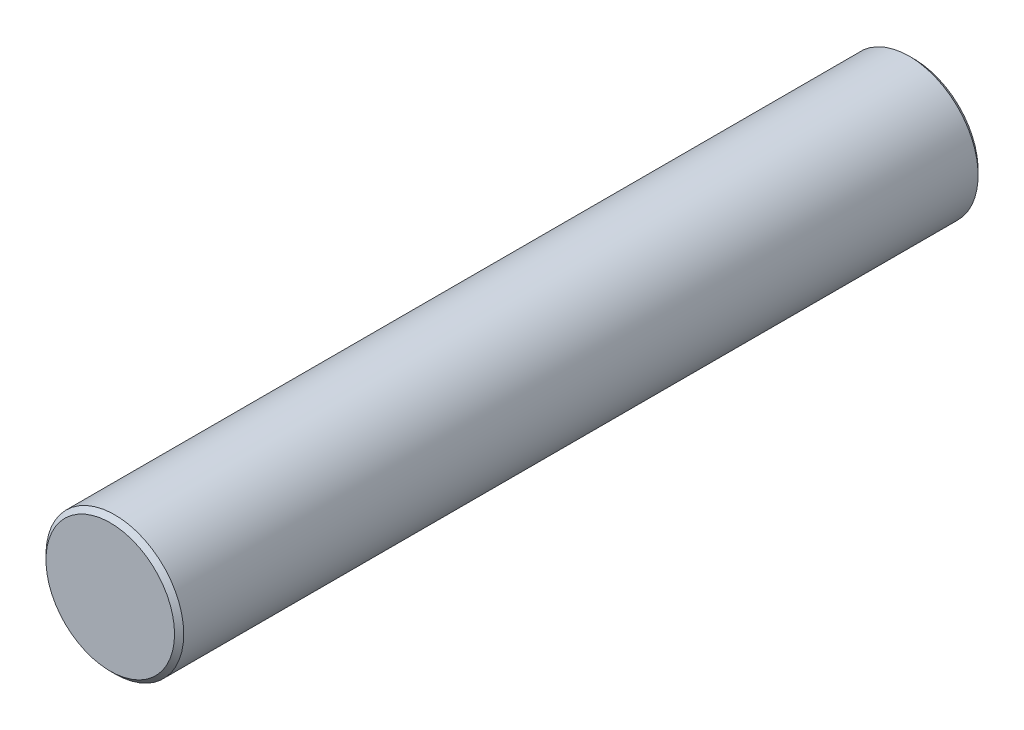
SolidWorks part; units mm, degrees
material "Chrome Stainless Steel"
ref_plane "Front Plane" through (0, 0, 0) normal (0, 0, 1) x (1, 0, 0)
ref_plane "Top Plane" through (0, 0, 0) normal (0, 1, 0) x (1, 0, 0)
ref_plane "Right Plane" through (0, 0, 0) normal (1, 0, 0) x (0, 0, -1)
sketch "Sketch1" plane through (0, 0, 0) normal (0, 0, 1) x (1, 0, 0)
  circle A0 centre (0, 0) radius 3
  dimension "D1" = 6
extrude "Boss-Extrude1" add sketch "Sketch1" along normal blind 35
ref_plane "Plane1" through (-3, 0, 0) normal (-1, 0, 0) x (0, 0, 1)
sketch "Sketch2" plane through (-3, 0, 0) normal (-1, 0, 0) x (0, 0, 1)
  line L0 (0, 0) -> (10, 0) construction
  line L2 (0, 3) -> (10, 3)
  line L3 (0, 3) -> (0, -3)
  line L4 (0, -3) -> (10, -3)
  line L5 (10, 3) -> (10, -3)
  line L6 (0, 3) -> (10, -3) construction
  line L7 (0, -3) -> (10, 3) construction
  point P3 (5, 0)
  dimension "D1" = 10
  dimension "D2" = 6
extrude "Cut-Extrude1" cut sketch "Sketch2" against normal blind 1
chamfer "Chamfer1" distance 0.2 angle 45 4 edges at (3, 0, 35) (-3, 0, 10) (-2, 0, 0) (3, 0, 0)
sketch "Sketch3" plane through (0, 0, 0) normal (0, 0, -1) x (-1, 0, 0)
  circle A0 centre (0, 0) radius 0.3
extrude "Cut-Extrude2" cut sketch "Sketch3" against normal blind 0.4 draft 15
